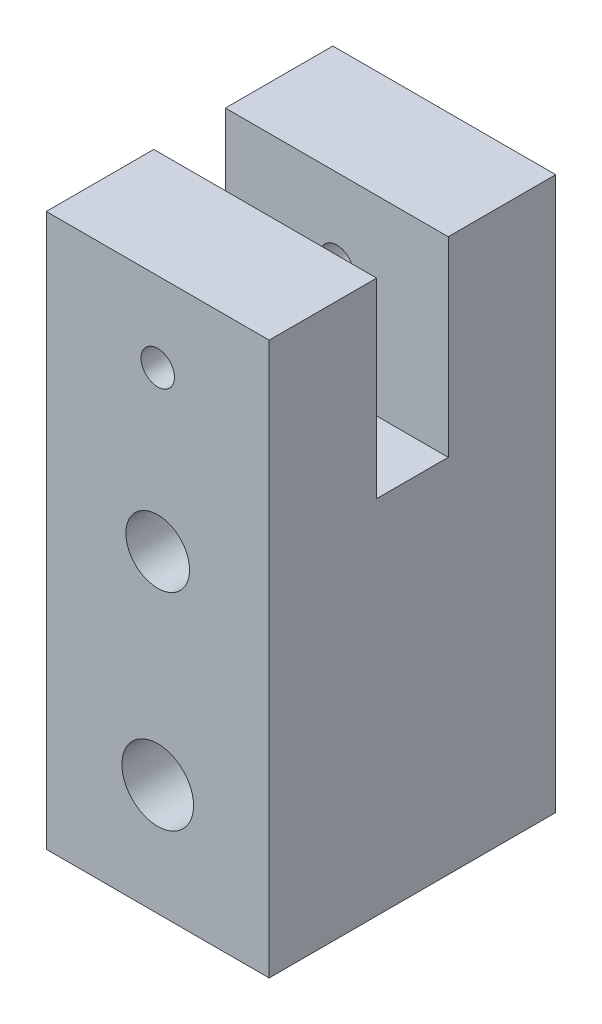
SolidWorks part; units mm, degrees
ref_plane "Front Plane" through (0, 0, 0) normal (0, 0, 1) x (1, 0, 0)
ref_plane "Top Plane" through (0, 0, 0) normal (0, 1, 0) x (1, 0, 0)
ref_plane "Right Plane" through (0, 0, 0) normal (1, 0, 0) x (0, 0, -1)
sketch "Sketch2" plane through (0, 0, 0) normal (0, 0, 1) x (1, 0, 0)
  line L1 (-7, -17.35) -> (7, -17.35)
  line L2 (-7, -17.35) -> (-7, 17.35)
  line L3 (-7, 17.35) -> (7, 17.35)
  line L4 (7, -17.35) -> (7, 17.35)
  line L5 (-7, -17.35) -> (7, 17.35) construction
  line L6 (-7, 17.35) -> (7, -17.35) construction
  point P0 (0, 0)
  dimension "D1" = 14
  dimension "D2" = 34.7
extrude "Boss-Extrude1" add sketch "Sketch2" along normal blind 18
sketch "Sketch3" plane through (0, 0, 18) normal (0, 0, 1) x (1, 0, 0)
  line L0 (-7, -17.35) -> (7, -17.35) construction
  circle A0 centre (0, -10.35) radius 2.25
  circle A1 centre (0, 2.35) radius 2
  dimension "D1" = 7
  dimension "D2" = 12.7
extrude "Cut-Extrude1" cut sketch "Sketch3" against normal through all
sketch "Sketch4" plane through (7, 0, 0) normal (1, 0, 0) x (0, 0, -1)
  line L0 (-18, 17.35) -> (0, 17.35) construction
  line L1 (-11.25, 5.35) -> (-6.75, 5.35)
  line L2 (-11.25, 5.35) -> (-11.25, 17.35)
  line L3 (-11.25, 17.35) -> (-6.75, 17.35)
  line L4 (-6.75, 5.35) -> (-6.75, 17.35)
  line L5 (-11.25, 5.35) -> (-6.75, 17.35) construction
  line L6 (-11.25, 17.35) -> (-6.75, 5.35) construction
  line L7 (0, -17.35) -> (0, 17.35) construction
  point P0 (-9, 11.35)
  dimension "D1" = 4.5
  dimension "D2" = 6.75
  dimension "D3" = 12
extrude "Cut-Extrude2" cut sketch "Sketch4" against normal blind 8
sketch "Sketch5" plane through (0, 0, 18) normal (0, 0, 1) x (1, 0, 0)
  line L0 (7, 17.35) -> (-7, 17.35) construction
  circle A0 centre (0, 12.35) radius 1.05
  dimension "D1" = 5
extrude "Cut-Extrude3" cut sketch "Sketch5" against normal through all
sketch "Sketch8" plane through (7, 0, 0) normal (1, 0, 0) x (0, 0, -1)
  line L0 (-11.25, 17.35) -> (-11.25, 5.35) construction
  line L1 (-6.75, 17.35) -> (-11.25, 17.35)
  line L2 (-6.75, 17.35) -> (-6.75, 10.35)
  line L3 (-6.75, 10.35) -> (-11.25, 10.35)
  line L4 (-11.25, 17.35) -> (-11.25, 10.35)
  dimension "D1" = 7
extrude "Cut-Extrude6" cut sketch "Sketch8" against normal through all
